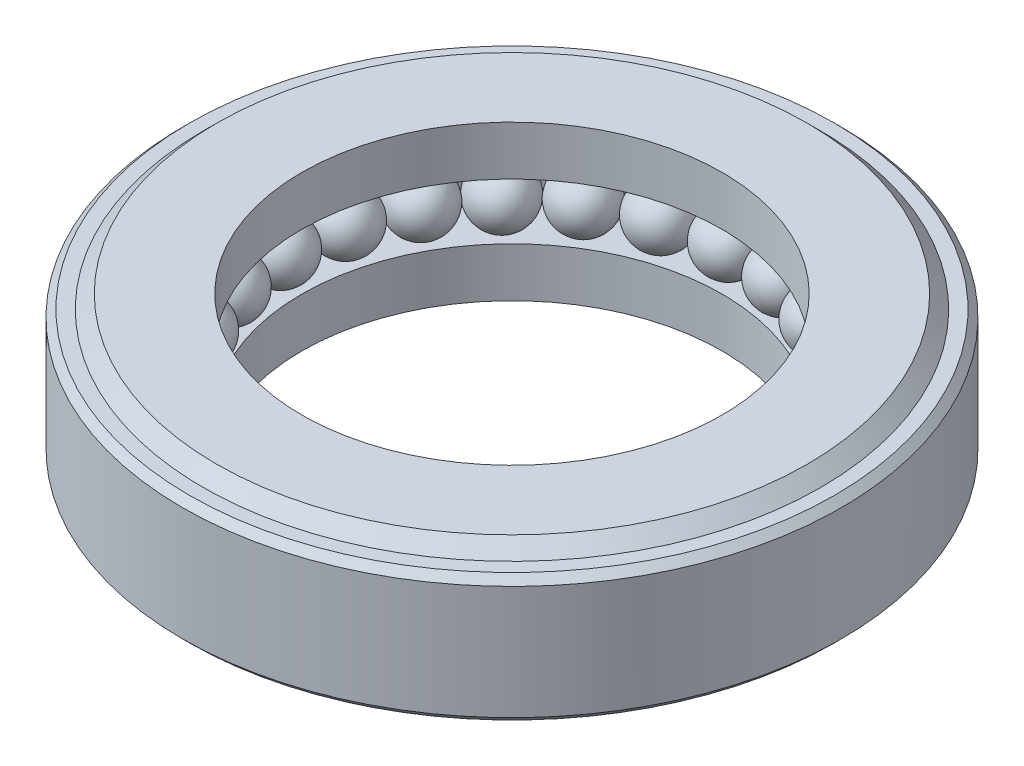
SolidWorks part; units mm, degrees
ref_plane "Front Plane" through (0, 0, 0) normal (0, 0, 1) x (1, 0, 0)
ref_plane "Top Plane" through (0, 0, 0) normal (0, 1, 0) x (1, 0, 0)
ref_plane "Right Plane" through (0, 0, 0) normal (1, 0, 0) x (0, 0, -1)
sketch "Sketch1" plane through (0, 0, 0) normal (0, 0, 1) x (1, 0, 0)
  line L0 (0, 0) -> (0.76, 0)
  line L1 (0.76, 0) -> (0.88, 0.12)
  line L2 (0.88, 0.12) -> (1.065, 0.12)
  line L3 (0.88, 1.26) -> (0.76, 1.38)
  line L4 (0.76, 1.38) -> (0, 1.38)
  line L5 (0, 1.38) -> (0, 0.94)
  line L6 (0, 0.94) -> (0.52, 0.94)
  line L7 (0.52, 0.94) -> (0.52, 0.44)
  line L8 (0.52, 0.44) -> (0, 0.44)
  line L9 (0, 0.44) -> (0, 0)
  line L10 (-1.875, 3.7211) -> (-1.875, -2.7541) construction
  line L11 (1.065, 0.12) -> (1.065, 1.26)
  line L12 (1.065, 1.26) -> (0.88, 1.26)
  point P3 (0, 0)
  point P11 (0, 0)
  point P17 (0.8854, 0)
  point P18 (0, 0)
  point P19 (0, 0)
  point P20 (0, 0)
  point P21 (0, 0)
  point P22 (0, 0)
  point P23 (0.52, 0.69)
  point P24 (1.065, 0.69)
  dimension "D1" = 1.38
  dimension "D2" = 2.755
  dimension "D3" = 0.5
  dimension "D4" = 2.94
  dimension "D5" = 1.875
  dimension "D6" = 2.635
  dimension "D7" = 1.14
  dimension "D8" = 2.395
revolve "Revolve1" add sketch "Sketch1" angle 360 about L10
sketch "Sketch2" plane through (0, 0, 0) normal (0, 0, 1) x (1, 0, 0)
  line L0 (0.76, 1.38) -> (-4.51, 1.38) construction
  line L1 (-3.9399, 0.43) -> (-3.9399, 0.95)
  arc A0 (-3.9399, 0.95) -> (-3.9399, 0.43) centre (-3.9399, 0.69) ccw
  point P9 (-3.9399, 0.69)
  dimension "D1" = 0.52
  dimension "D2" = 0.69
revolve "Revolve2" add sketch "Sketch2" angle 360 about L1
pattern_circular "CirPattern1" count 25 over 360 about axis through (-1.875, 0, 0) along (0, 1, 0) of "Revolve2"
chamfer "Chamfer1" distance 0.063 angle 45 2 edges at (-4.815, 0.12, 0) (-4.815, 1.26, 0)
